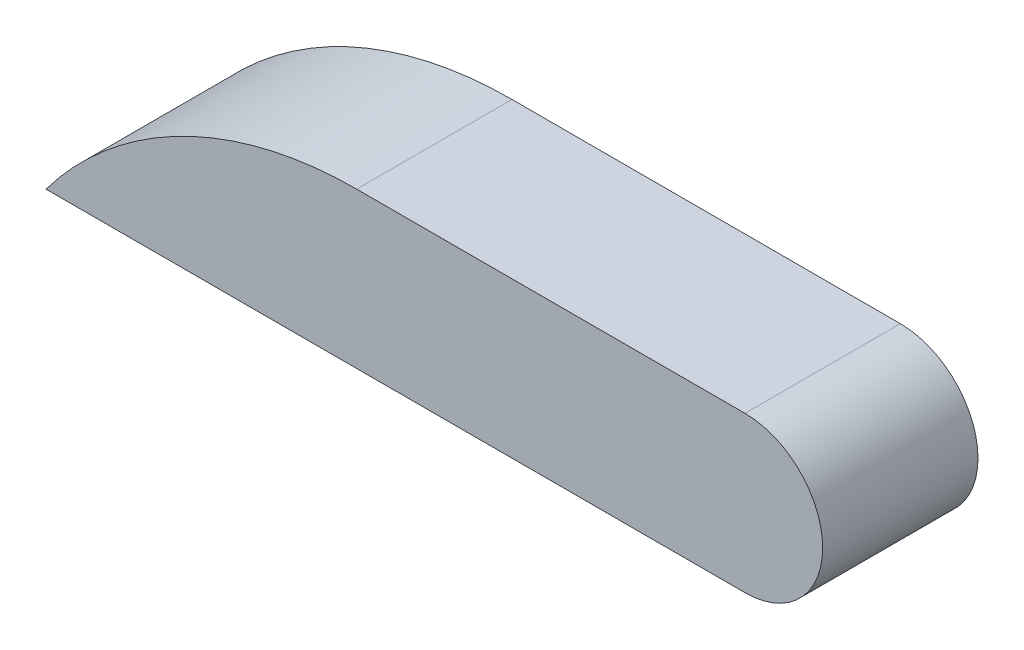
SolidWorks part; units mm, degrees
ref_plane "Front" through (0, 0, 0) normal (0, 0, 1) x (1, 0, 0)
ref_plane "Top" through (0, 0, 0) normal (0, 1, 0) x (1, 0, 0)
ref_plane "Right" through (0, 0, 0) normal (1, 0, 0) x (0, 0, -1)
sketch "Sketch1" plane through (0, 0, 0) normal (0, 0, 1) x (1, 0, 0)
  line L1 (11.43, 0) -> (0, 0)
  line L3 (11.43, 2.54) -> (5.08, 2.54)
  arc A0 (11.43, 0) -> (11.43, 2.54) centre (11.43, 1.27) ccw
  arc A1 (5.08, 2.54) -> (0, 0) centre (5.08, -3.81) ccw
  point P0 (0, 0)
  point P6 (0, 0)
  point P10 (0, 0)
  point P11 (0, 0)
  point P12 (0, 0.2794)
  point P13 (0, 0)
  point P14 (0, 0)
  point P15 (0, 0)
  point P16 (0, 0)
  dimension "D1" = 5.08
  dimension "D2" = 11.43
  dimension "D7" = 2.54
extrude "Boss-Extrude1" add sketch "Sketch1" along normal blind 2.54
sketch "Sketch2" plane through (0, 0, 2.54) normal (0, 0, 1) x (1, 0, 0)
  circle A0 centre (11.43, 1.27) radius 0.4445
  arc A2 (11.43, 0) -> (11.43, 2.54) centre (11.43, 1.27) ccw construction
  point P4 (0, 0)
  dimension "D1" = 0.889
